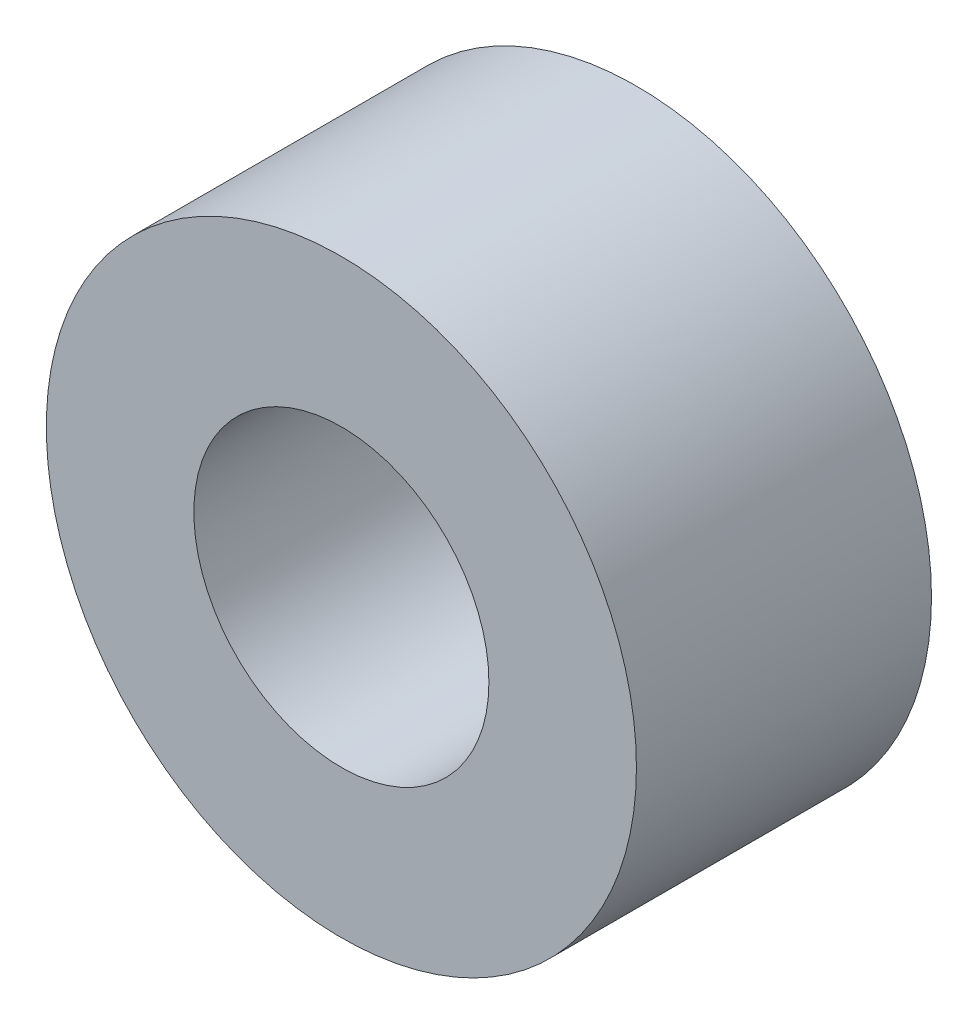
SolidWorks part; units mm, degrees
ref_plane "前视基准面" through (0, 0, 0) normal (0, 0, 1) x (1, 0, 0)
ref_plane "上视基准面" through (0, 0, 0) normal (0, 1, 0) x (1, 0, 0)
ref_plane "右视基准面" through (0, 0, 0) normal (1, 0, 0) x (0, 0, -1)
other "Configuration Table"
sketch "草图1" plane through (0, 0, 0) normal (0, 0, 1) x (1, 0, 0)
  circle A0 centre (-18.6899, 1.1287) radius 5
  circle A2 centre (-18.6899, 1.1287) radius 2.5
  point P3 (-10.3959, 0.382)
  point P4 (-18.6899, 1.1287)
  dimension "D1" = 10
  dimension "D2" = 5
extrude "凸台-拉伸1" add sketch "草图1" along normal blind 5
